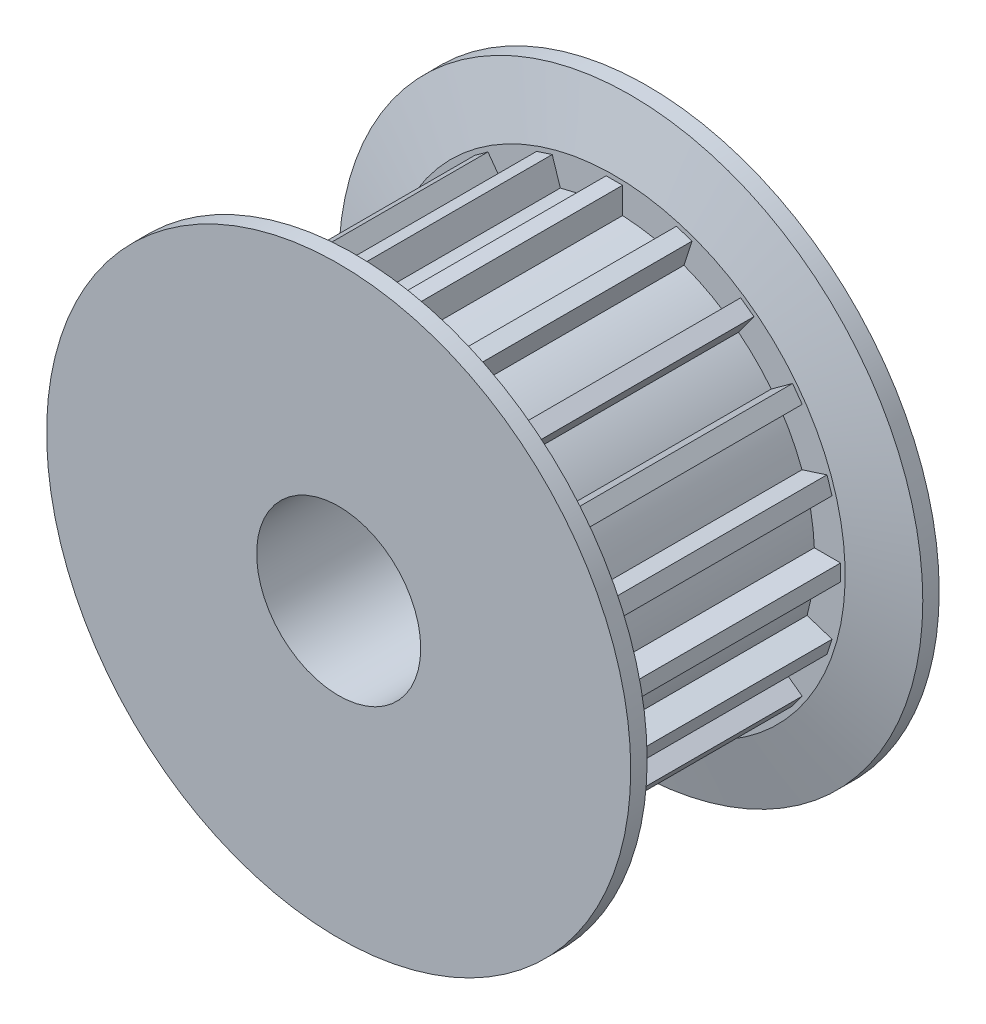
SolidWorks part; units mm, degrees
ref_plane "Front Plane" through (0, 0, 0) normal (0, 0, 1) x (1, 0, 0)
ref_plane "Top Plane" through (0, 0, 0) normal (0, 1, 0) x (1, 0, 0)
ref_plane "Right Plane" through (0, 0, 0) normal (1, 0, 0) x (0, 0, -1)
sketch "Sketch2" plane through (0, 0, 0) normal (1, 0, 0) x (0, 0, -1)
  line L0 (-16, 2.5) -> (-6.6, 2.5)
  line L2 (-6.6, 8.9) -> (-7.6, 8.9)
  line L3 (-7.6, 8.9) -> (-7.6, 6.1)
  line L4 (-7.6, 6.1) -> (-15, 6.1)
  line L5 (-15, 6.1) -> (-15, 8.9)
  line L6 (-15, 8.9) -> (-16, 8.9)
  line L7 (-16, 8.9) -> (-16, 2.5)
  line L8 (-79.6095, 0) -> (75.5553, 0) construction
  line L9 (-6.6, 8.9) -> (-6.6, 2.5)
  dimension "D1" = 1
  dimension "D2" = 8.9
  dimension "D3" = 1
  dimension "D4" = 7.4
  dimension "D5" = 2.5
  dimension "D6" = 6.1
  dimension "D7" = 6.6
revolve "Revolve1" add sketch "Sketch2" angle 360 about L8
chamfer "Chamfer1" distance 0.5 angle 75 1 edges at (8.9, 0, 15)
chamfer "Chamfer2" distance 0.5 angle 75 1 edges at (8.9, 0, 7.6)
sketch "Sketch4" plane through (0, 0, 7.6) normal (0, 0, 1) x (1, 0, 0)
  line L0 (1.6457, 5.8738) -> (1.8929, 6.6347)
  line L1 (1.8929, 6.6347) -> (2.3684, 6.4802)
  line L2 (-0.25, 6.0949) -> (-0.25, 6.8949)
  line L3 (-0.25, 6.8949) -> (0.25, 6.8949)
  line L4 (0.25, 6.0949) -> (0.25, 6.8949)
  line L5 (2.1212, 5.7193) -> (2.3684, 6.4802)
  line L6 (3.3802, 5.0778) -> (3.8505, 5.725)
  line L7 (3.8505, 5.725) -> (4.255, 5.4311)
  line L8 (3.7847, 4.7839) -> (4.255, 5.4311)
  line L9 (4.7839, 3.7847) -> (5.4311, 4.255)
  line L10 (5.4311, 4.255) -> (5.725, 3.8505)
  line L11 (5.0778, 3.3802) -> (5.725, 3.8505)
  line L12 (5.7193, 2.1212) -> (6.4802, 2.3684)
  line L13 (6.4802, 2.3684) -> (6.6347, 1.8929)
  line L14 (5.8738, 1.6457) -> (6.6347, 1.8929)
  line L15 (6.0949, 0.25) -> (6.8949, 0.25)
  line L16 (6.8949, 0.25) -> (6.8949, -0.25)
  line L17 (6.0949, -0.25) -> (6.8949, -0.25)
  line L18 (5.8738, -1.6457) -> (6.6347, -1.8929)
  line L19 (6.6347, -1.8929) -> (6.4802, -2.3684)
  line L20 (5.7193, -2.1212) -> (6.4802, -2.3684)
  line L21 (5.0778, -3.3802) -> (5.725, -3.8505)
  line L22 (5.725, -3.8505) -> (5.4311, -4.255)
  line L23 (4.7839, -3.7847) -> (5.4311, -4.255)
  line L24 (3.7847, -4.7839) -> (4.255, -5.4311)
  line L25 (4.255, -5.4311) -> (3.8505, -5.725)
  line L26 (3.3802, -5.0778) -> (3.8505, -5.725)
  line L27 (2.1212, -5.7193) -> (2.3684, -6.4802)
  line L28 (2.3684, -6.4802) -> (1.8929, -6.6347)
  line L29 (1.6457, -5.8738) -> (1.8929, -6.6347)
  line L30 (0.25, -6.0949) -> (0.25, -6.8949)
  line L31 (0.25, -6.8949) -> (-0.25, -6.8949)
  line L32 (-0.25, -6.0949) -> (-0.25, -6.8949)
  line L33 (-1.6457, -5.8738) -> (-1.8929, -6.6347)
  line L34 (-1.8929, -6.6347) -> (-2.3684, -6.4802)
  line L35 (-2.1212, -5.7193) -> (-2.3684, -6.4802)
  line L36 (-3.3802, -5.0778) -> (-3.8505, -5.725)
  line L37 (-3.8505, -5.725) -> (-4.255, -5.4311)
  line L38 (-3.7847, -4.7839) -> (-4.255, -5.4311)
  line L39 (-4.7839, -3.7847) -> (-5.4311, -4.255)
  line L40 (-5.4311, -4.255) -> (-5.725, -3.8505)
  line L41 (-5.0778, -3.3802) -> (-5.725, -3.8505)
  line L42 (-5.7193, -2.1212) -> (-6.4802, -2.3684)
  line L43 (-6.4802, -2.3684) -> (-6.6347, -1.8929)
  line L44 (-5.8738, -1.6457) -> (-6.6347, -1.8929)
  line L45 (-6.0949, -0.25) -> (-6.8949, -0.25)
  line L46 (-6.8949, -0.25) -> (-6.8949, 0.25)
  line L47 (-6.0949, 0.25) -> (-6.8949, 0.25)
  line L48 (-5.8738, 1.6457) -> (-6.6347, 1.8929)
  line L49 (-6.6347, 1.8929) -> (-6.4802, 2.3684)
  line L50 (-5.7193, 2.1212) -> (-6.4802, 2.3684)
  line L51 (-5.0778, 3.3802) -> (-5.725, 3.8505)
  line L52 (-5.725, 3.8505) -> (-5.4311, 4.255)
  line L53 (-4.7839, 3.7847) -> (-5.4311, 4.255)
  line L54 (-3.7847, 4.7839) -> (-4.255, 5.4311)
  line L55 (-4.255, 5.4311) -> (-3.8505, 5.725)
  line L56 (-3.3802, 5.0778) -> (-3.8505, 5.725)
  line L57 (-2.1212, 5.7193) -> (-2.3684, 6.4802)
  line L58 (-2.3684, 6.4802) -> (-1.8929, 6.6347)
  line L59 (-1.6457, 5.8738) -> (-1.8929, 6.6347)
  arc A0 (-3.3802, 5.0778) -> (-3.7847, 4.7839) centre (0, 0) ccw
  arc A1 (-1.6457, 5.8738) -> (-2.1212, 5.7193) centre (0, 0) ccw
  arc A2 (0.25, 6.0949) -> (-0.25, 6.0949) centre (0, 0) ccw
  arc A3 (2.1212, 5.7193) -> (1.6457, 5.8738) centre (0, 0) ccw
  arc A4 (3.7847, 4.7839) -> (3.3802, 5.0778) centre (0, 0) ccw
  arc A5 (5.0778, 3.3802) -> (4.7839, 3.7847) centre (0, 0) ccw
  arc A6 (5.8738, 1.6457) -> (5.7193, 2.1212) centre (0, 0) ccw
  arc A7 (6.0949, -0.25) -> (6.0949, 0.25) centre (0, 0) ccw
  arc A8 (5.7193, -2.1212) -> (5.8738, -1.6457) centre (0, 0) ccw
  arc A9 (4.7839, -3.7847) -> (5.0778, -3.3802) centre (0, 0) ccw
  arc A10 (3.3802, -5.0778) -> (3.7847, -4.7839) centre (0, 0) ccw
  arc A11 (1.6457, -5.8738) -> (2.1212, -5.7193) centre (0, 0) ccw
  arc A12 (-0.25, -6.0949) -> (0.25, -6.0949) centre (0, 0) ccw
  arc A13 (-2.1212, -5.7193) -> (-1.6457, -5.8738) centre (0, 0) ccw
  arc A14 (-3.7847, -4.7839) -> (-3.3802, -5.0778) centre (0, 0) ccw
  arc A15 (-5.0778, -3.3802) -> (-4.7839, -3.7847) centre (0, 0) ccw
  arc A16 (-5.8738, -1.6457) -> (-5.7193, -2.1212) centre (0, 0) ccw
  arc A17 (-6.0949, 0.25) -> (-6.0949, -0.25) centre (0, 0) ccw
  arc A18 (-5.7193, 2.1212) -> (-5.8738, 1.6457) centre (0, 0) ccw
  arc A19 (-4.7839, 3.7847) -> (-5.0778, 3.3802) centre (0, 0) ccw
  dimension "D1" = 12.2
  dimension "D2" = 0.5
  dimension "D3" = 0.25
  dimension "D4" = 0.8
  dimension "D5" = 20
extrude "Boss-Extrude1" add sketch "Sketch4" along normal up to surface (7.4 mm away) up to face at (7.034, 0, 15)
ref_plane "Plane1" through (0, 8.9, 0) normal (0, 1, 0) x (-1, 0, 0)
